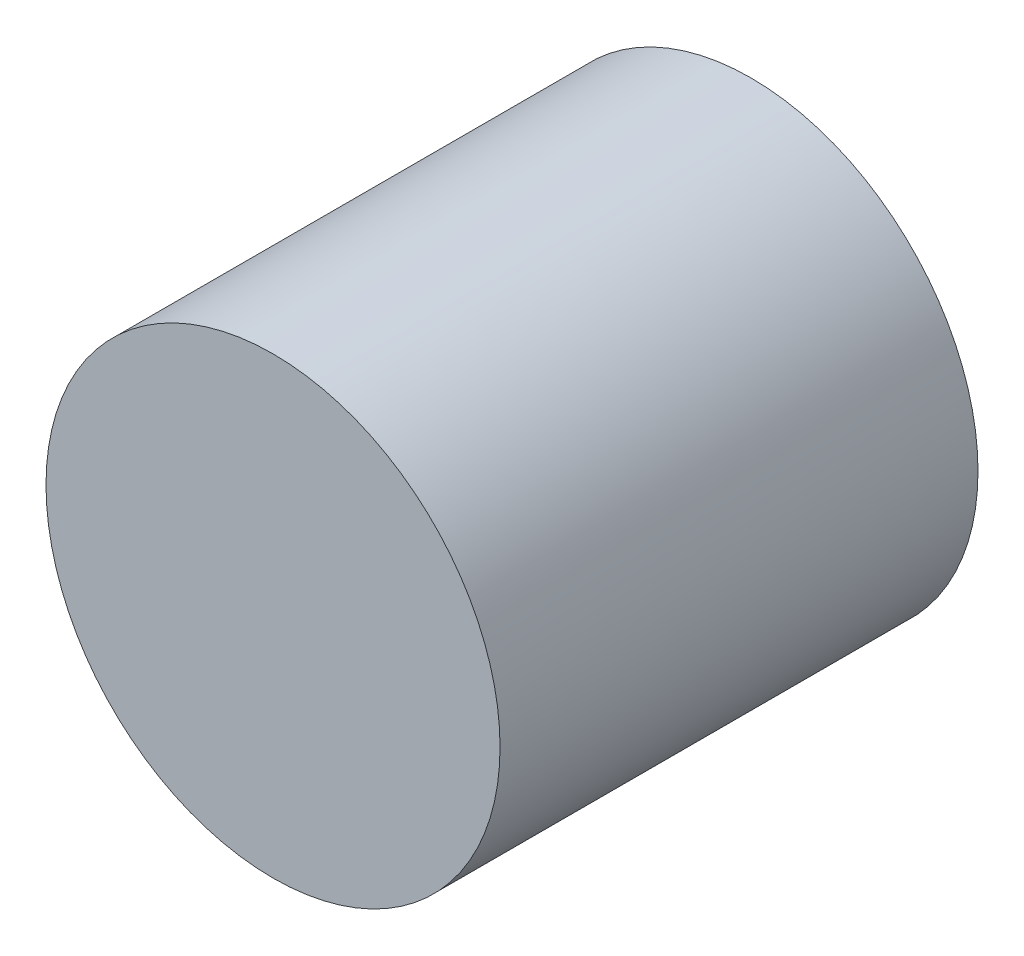
SolidWorks part; units mm, degrees
ref_plane "Front Plane" through (0, 0, 0) normal (0, 0, 1) x (1, 0, 0)
ref_plane "Top Plane" through (0, 0, 0) normal (0, 1, 0) x (1, 0, 0)
ref_plane "Right Plane" through (0, 0, 0) normal (1, 0, 0) x (0, 0, -1)
sketch "Sketch1" plane through (0, 0, 0) normal (0, 0, 1) x (1, 0, 0)
  circle A0 centre (0, 0) radius 4.826
  dimension "D1" = 9.652
extrude "Boss-Extrude1" add sketch "Sketch1" along normal mid plane 10.16
